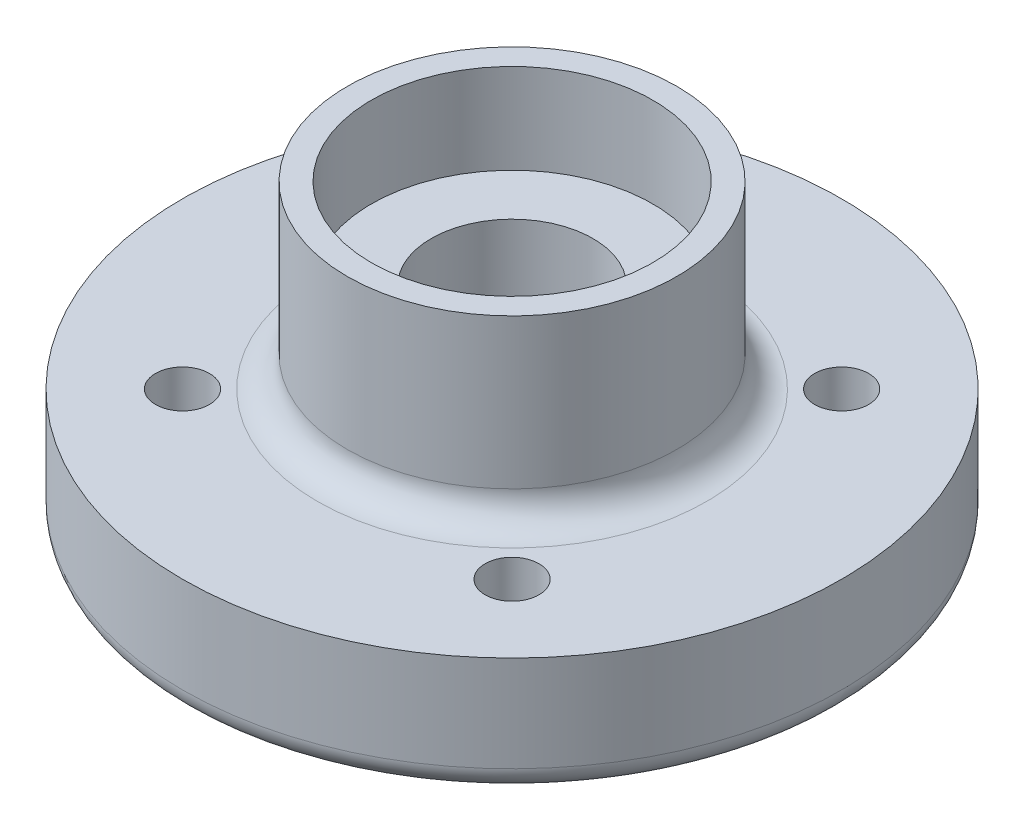
SolidWorks part; units mm, degrees
ref_plane "Front Plane" through (0, 0, 0) normal (0, 0, 1) x (1, 0, 0)
ref_plane "Top Plane" through (0, 0, 0) normal (0, 1, 0) x (1, 0, 0)
ref_plane "Right Plane" through (0, 0, 0) normal (1, 0, 0) x (0, 0, -1)
sketch "Sketch1" plane through (0, 0, 0) normal (0, 1, 0) x (1, 0, 0)
  circle A0 centre (0, 0) radius 55
  dimension "D1" = 110
extrude "Boss-Extrude1" add sketch "Sketch1" along normal blind 20
sketch "Sketch2" plane through (0, 20, 0) normal (0, 1, 0) x (1, 0, 0)
  circle A0 centre (0, 0) radius 27.5
  dimension "D1" = 55
extrude "Boss-Extrude2" add sketch "Sketch2" along normal blind 30
sketch "Sketch6" plane through (0, 50, 0) normal (0, 1, 0) x (1, 0, 0)
  circle A2 centre (0, 0) radius 23.5
  circle A3 centre (0, 0) radius 23.5
  dimension "D1" = 4
extrude "Cut-Extrude1" cut sketch "Sketch6" against normal blind 15
fillet "Fillet1" radius 5 1 edges at (0, 20, 27.5)
sketch "Sketch7" plane through (0, 0, 0) normal (0, -1, 0) x (1, 0, 0)
  line L1 (-27.5, 27.5) -> (27.5, 27.5) construction
  line L2 (-27.5, 27.5) -> (-27.5, -27.5) construction
  line L3 (-27.5, -27.5) -> (27.5, -27.5) construction
  line L4 (27.5, 27.5) -> (27.5, -27.5) construction
  line L5 (-27.5, 27.5) -> (27.5, -27.5) construction
  line L6 (-27.5, -27.5) -> (27.5, 27.5) construction
  point P0 (0, 0)
  point P9 (0, 0)
  dimension "D1" = 55
  dimension "D2" = 55
hole_wizard "CBORE for M8 Hex Head Bolt1" positions "3DSketch1" profile "Sketch12" counterbore size "M8" standard "ISO" end condition through all
sketch3d "3DSketch1"
  point P0 (-27.5, 0, 27.5)
  point P3 (27.5, 0, 27.5)
  point P6 (27.5, 0, -27.5)
  point P9 (-27.5, 0, -27.5)
sketch "Sketch12" plane through (-27.5, 0, 27.5) normal (1, 0, 0) x (0, 0, -1)
  line L0 (0, 0) -> (0, 50)
  line L1 (0, 50) -> (4.5, 50)
  line L3 (4.5, 50) -> (4.5, 5.3)
  line L4 (4.5, 5.3) -> (9.0055, 5.3)
  line L5 (9.0055, 5.3) -> (9.0055, 0)
  line L7 (9.0055, 0) -> (0, 0)
  line L11 (0, -6.35) -> (0, 107.95) construction
  dimension "Thru Hole Dia." = 9
  dimension "Thru Hole Depth" = 50
  dimension "C'Bore Dia." = 18.011
  dimension "C'Bore Depth" = 5.3
fillet "Fillet2" radius 4 1 edges at (0, 0, 55)
sketch "Sketch10" plane through (0, 35, 0) normal (0, 1, 0) x (1, 0, 0)
  circle A1 centre (0, 0) radius 13.5
  dimension "D1" = 27
extrude "Cut-Extrude2" cut sketch "Sketch10" against normal blind 53
sketch "Sketch11" plane through (0, 0, 0) normal (0, -1, 0) x (1, 0, 0)
  circle A0 centre (0, 0) radius 22.5
  circle A1 centre (0, 0) radius 13.5 construction
  circle A2 centre (0, 0) radius 13.5
  dimension "D1" = 45
extrude "Boss-Extrude3" add sketch "Sketch11" along normal blind 15 contours A0 | A2
fillet "Fillet3" radius 5 2 edges at (0, 0, 22.5) (0, -15, -22.5)
